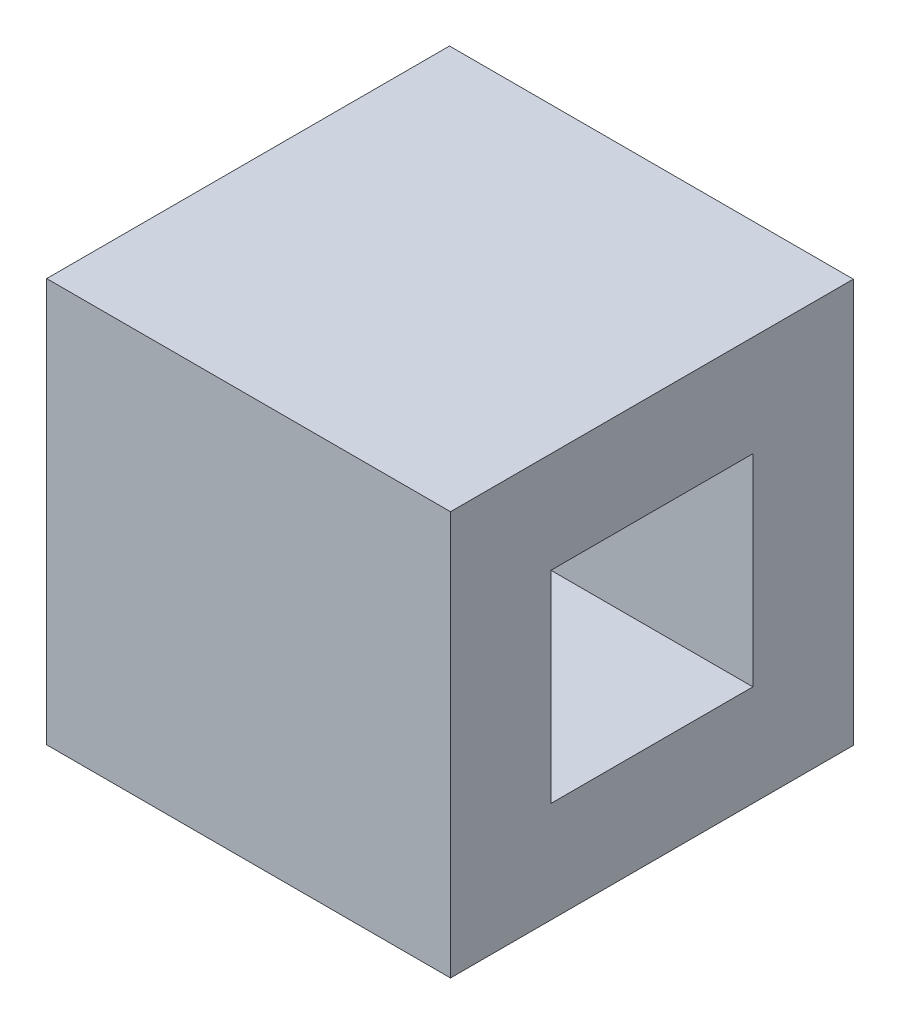
SolidWorks part; units mm, degrees
ref_plane "前视基准面" through (0, 0, 0) normal (0, 0, 1) x (1, 0, 0)
ref_plane "上视基准面" through (0, 0, 0) normal (0, 1, 0) x (1, 0, 0)
ref_plane "右视基准面" through (0, 0, 0) normal (1, 0, 0) x (0, 0, -1)
other "Configuration Table"
sketch "草图1" plane through (0, 0, 0) normal (0, 1, 0) x (1, 0, 0)
  line L1 (0, 0) -> (-40, 0)
  line L2 (0, 0) -> (0, 39.9)
  line L3 (0, 39.9) -> (-40, 39.9)
  line L4 (-40, 0) -> (-40, 39.9)
  dimension "D1" = 39.9
  dimension "D2" = 40
extrude "凸台-拉伸1" add sketch "草图1" along normal blind 40
sketch "草图3" plane through (0, 0, 0) normal (1, 0, 0) x (0, 0, -1)
  line L0 (0, 40) -> (39.9, 0) construction
  line L2 (29.95, 30) -> (9.95, 30)
  line L3 (29.95, 30) -> (29.95, 10)
  line L4 (29.95, 10) -> (9.95, 10)
  line L5 (9.95, 30) -> (9.95, 10)
  line L6 (29.95, 30) -> (9.95, 10) construction
  line L7 (29.95, 10) -> (9.95, 30) construction
  point P4 (19.95, 20)
  dimension "D1" = 20
  dimension "D2" = 20
extrude "切除-拉伸1" cut sketch "草图3" against normal blind 20
